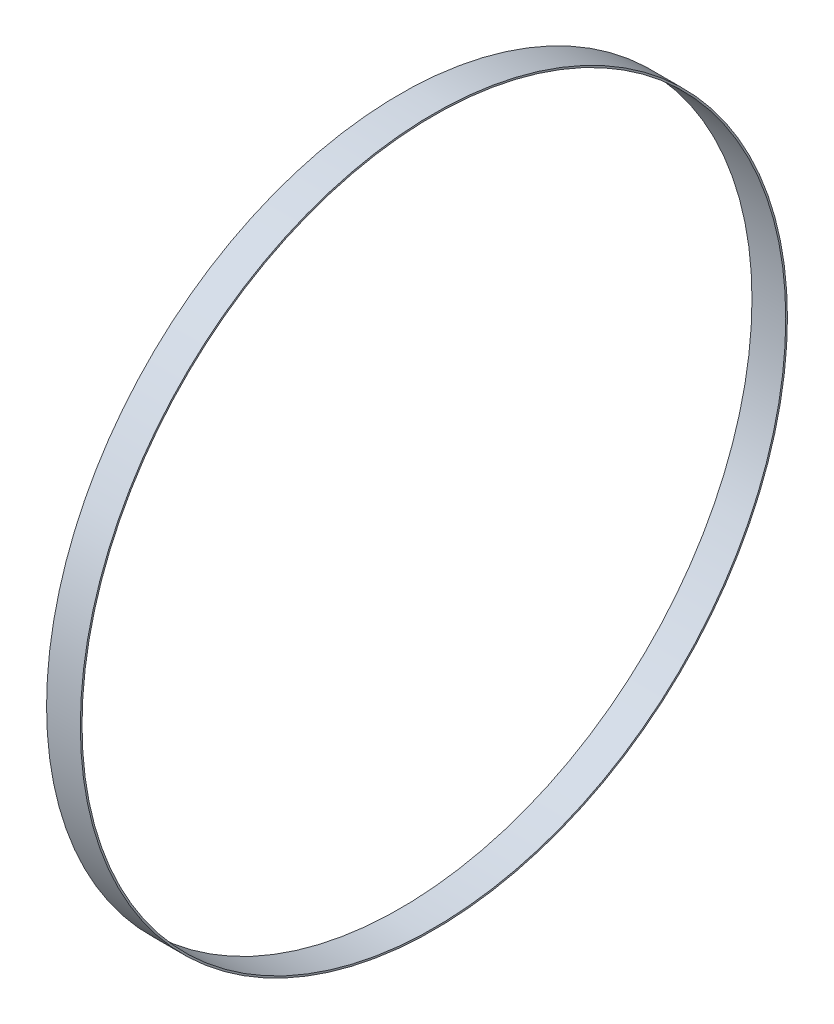
SolidWorks part; units mm, degrees
material "ASTM A36 Steel"
ref_plane "Front Plane" through (0, 0, 0) normal (0, 0, 1) x (1, 0, 0)
ref_plane "Top Plane" through (0, 0, 0) normal (0, 1, 0) x (1, 0, 0)
ref_plane "Right Plane" through (0, 0, 0) normal (1, 0, 0) x (0, 0, -1)
sketch "Sketch1" plane through (0, 0, 0) normal (1, 0, 0) x (0, 0, -1)
  circle A0 centre (0, 0) radius 1047
  circle A1 centre (0, 0) radius 1042
  dimension "D1" = 2094
  dimension "D2" = 5
extrude "Boss-Extrude1" add sketch "Sketch1" along normal blind 100
